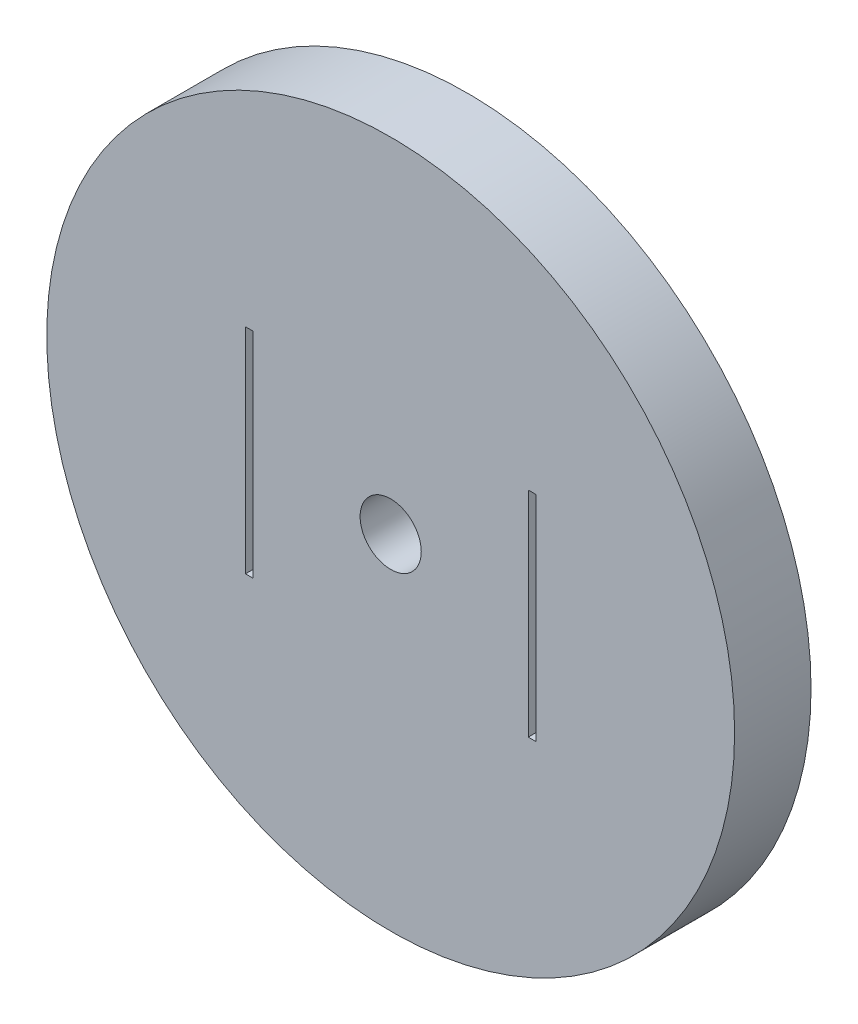
SolidWorks part; units mm, degrees
ref_plane "Front Plane" through (0, 0, 0) normal (0, 0, 1) x (1, 0, 0)
ref_plane "Top Plane" through (0, 0, 0) normal (0, 1, 0) x (1, 0, 0)
ref_plane "Right Plane" through (0, 0, 0) normal (1, 0, 0) x (0, 0, -1)
sketch "Sketch1" plane through (0, 0, 0) normal (0, 0, 1) x (1, 0, 0)
  line L0 (0, 10.3237) -> (0, -11.9962) construction
  line L1 (-9.5, 7) -> (-9, 7)
  line L2 (-9.5, 7) -> (-9.5, -7)
  line L3 (-9.5, -7) -> (-9, -7)
  line L4 (-9, 7) -> (-9, -7)
  line L5 (9, 7) -> (9, -7)
  line L6 (9.5, -7) -> (9, -7)
  line L7 (9.5, 7) -> (9.5, -7)
  line L8 (9.5, 7) -> (9, 7)
  circle A0 centre (0, 0) radius 22.5
  circle A1 centre (0, 0) radius 2
  dimension "D1" = 4
  dimension "D2" = 45
  dimension "D3" = 0.5
  dimension "D4" = 9
  dimension "D5" = 7
  dimension "D6" = 7
extrude "Boss-Extrude1" add sketch "Sketch1" along normal blind 5
sketch "Sketch3" plane through (0, 0, 0) normal (0, 1, 0) x (1, 0, 0)
  line L0 (-14.5, 6) -> (-14.5, 0) construction
  line L1 (22.5, 0) -> (-22.5, 0) construction
  line L2 (-17, 6) -> (-17, 0)
  line L3 (-17, 0) -> (-14.5, 0)
  line L4 (-14.5, 0) -> (-14.5, 8.5)
  line L5 (-22.5, 0) -> (-22.5, -5) construction
  circle A0 centre (-14.5, 6) radius 2.5 construction
  arc A1 (-17, 6) -> (-14.5, 8.5) centre (-14.5, 6) cw
  dimension "D1" = 5
  dimension "D2" = 8
  dimension "D3" = 8.5
revolve "Revolve1" add sketch "Sketch3" angle 360 about L0
